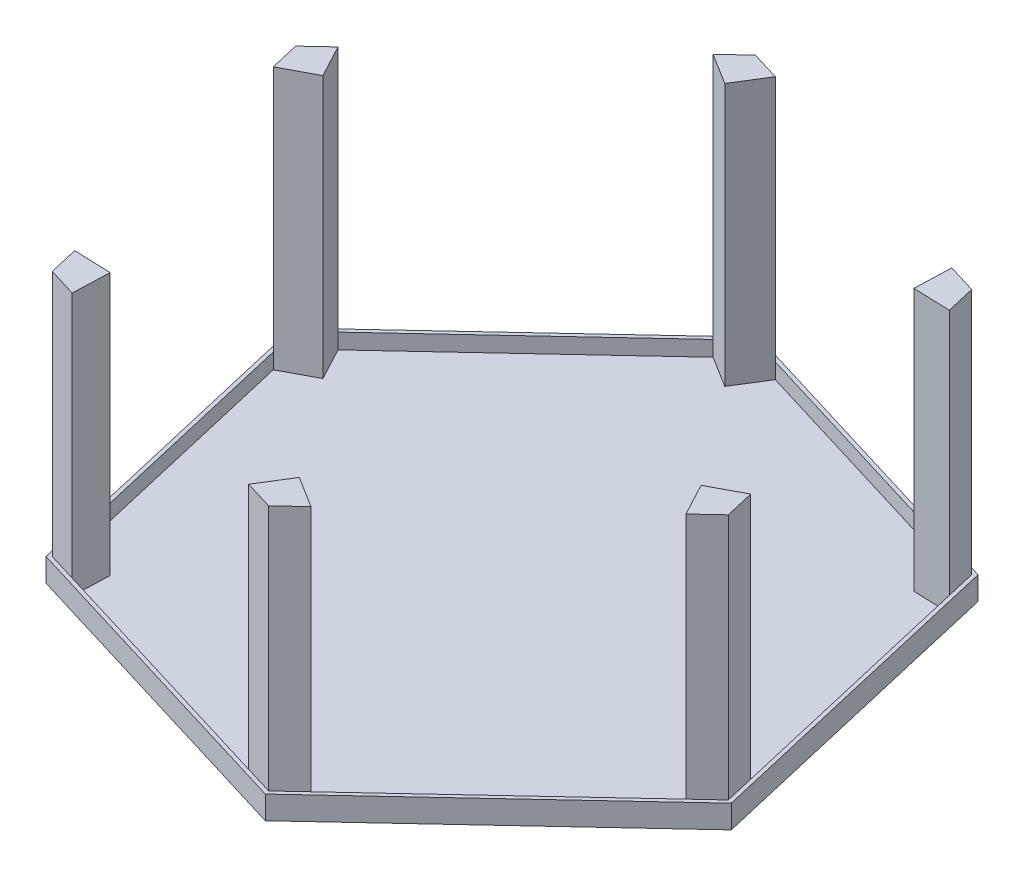
SolidWorks part; units mm, degrees
ref_plane "Plan de face" through (0, 0, 0) normal (0, 0, 1) x (1, 0, 0)
ref_plane "Plan de dessus" through (0, 0, 0) normal (0, 1, 0) x (1, 0, 0)
ref_plane "Plan de droite" through (0, 0, 0) normal (1, 0, 0) x (0, 0, -1)
sketch "Esquisse1" plane through (0, 0, 0) normal (0, 1, 0) x (1, 0, 0)
  line L1 (312.1988, 291.6594) -> (-96.4851, 416.2018)
  line L2 (-96.4851, 416.2018) -> (-408.6839, 124.5424)
  line L3 (-408.6839, 124.5424) -> (-312.1988, -291.6594)
  line L4 (-312.1988, -291.6594) -> (96.4851, -416.2018)
  line L5 (96.4851, -416.2018) -> (408.6839, -124.5424)
  line L6 (408.6839, -124.5424) -> (312.1988, 291.6594)
  circle A0 centre (0, 0) radius 370 construction
  dimension "D1" = 740
extrude "Boss.-Extru.1" add sketch "Esquisse1" along normal blind 30
sketch "Esquisse2" plane through (0, 30, 0) normal (0, 1, 0) x (1, 0, 0)
  line L12 (403.1611, -122.8594) -> (307.9799, 287.7181)
  line L13 (307.9799, 287.7181) -> (-95.1812, 410.5775)
  line L14 (-95.1812, 410.5775) -> (-403.1611, 122.8594)
  line L15 (-403.1611, 122.8594) -> (-307.9799, -287.7181)
  line L16 (-307.9799, -287.7181) -> (95.1812, -410.5775)
  line L17 (95.1812, -410.5775) -> (403.1611, -122.8594)
  line L18 (403.1611, -122.8594) -> (307.9799, 287.7181)
  line L19 (307.9799, 287.7181) -> (-95.1812, 410.5775)
  line L20 (-95.1812, 410.5775) -> (-403.1611, 122.8594)
  line L21 (-403.1611, 122.8594) -> (-307.9799, -287.7181)
  line L22 (-307.9799, -287.7181) -> (95.1812, -410.5775)
  line L23 (95.1812, -410.5775) -> (403.1611, -122.8594)
  dimension "D1" = 5
extrude "Enlèv. mat.-Extru.1" cut sketch "Esquisse2" against normal blind 20
sketch "Esquisse5" plane through (0, 10, 0) normal (0, 1, 0) x (1, 0, 0)
  line L0 (0, 0) -> (95.1812, -410.5775) construction
  line L2 (83.2046, -358.9145) -> (43.5183, -422.5541)
  line L3 (43.5183, -422.5541) -> (107.1579, -462.2404)
  line L4 (107.1579, -462.2404) -> (146.8442, -398.6008)
  line L5 (146.8442, -398.6008) -> (83.2046, -358.9145)
  circle A0 centre (95.1812, -410.5775) radius 37.5 construction
  dimension "D1" = 75
extrude "Boss.-Extru.3" add sketch "Esquisse5" along normal blind 340
sketch "Esquisse6" plane through (0, 350, 0) normal (0, 1, 0) x (1, 0, 0)
  line L0 (55.3054, -403.6527) -> (96.4851, -416.2018)
  line L1 (96.4851, -416.2018) -> (127.9428, -386.8137)
  line L2 (127.9428, -386.8137) -> (146.8442, -398.6008)
  line L3 (146.8442, -398.6008) -> (107.1579, -462.2404)
  line L4 (107.1579, -462.2404) -> (43.5183, -422.5541)
  line L5 (43.5183, -422.5541) -> (55.3054, -403.6527)
extrude "Enlèv. mat.-Extru.2" cut sketch "Esquisse6" against normal through all
sketch "Esquisse7" plane through (0, 350, 0) normal (0, 1, 0) x (1, 0, 0)
  line L0 (58.0445, -399.2604) -> (55.3054, -403.6527)
  line L1 (58.0445, -399.2604) -> (95.1812, -410.5775)
  line L2 (55.3054, -403.6527) -> (96.4851, -416.2018)
  line L4 (123.5504, -384.0746) -> (127.9428, -386.8137)
  line L5 (123.5504, -384.0746) -> (95.1812, -410.5775)
  line L6 (127.9428, -386.8137) -> (96.4851, -416.2018)
extrude "Enlèv. mat.-Extru.5" cut sketch "Esquisse7" against normal blind 320 and the other way blind 44
pattern_circular "Répétition circulaire13" count 6 over 360 about axis through (0, 0, 0) along (0, 1, 0) of "Boss.-Extru.3", "Enlèv. mat.-Extru.2", "Enlèv. mat.-Extru.5"
